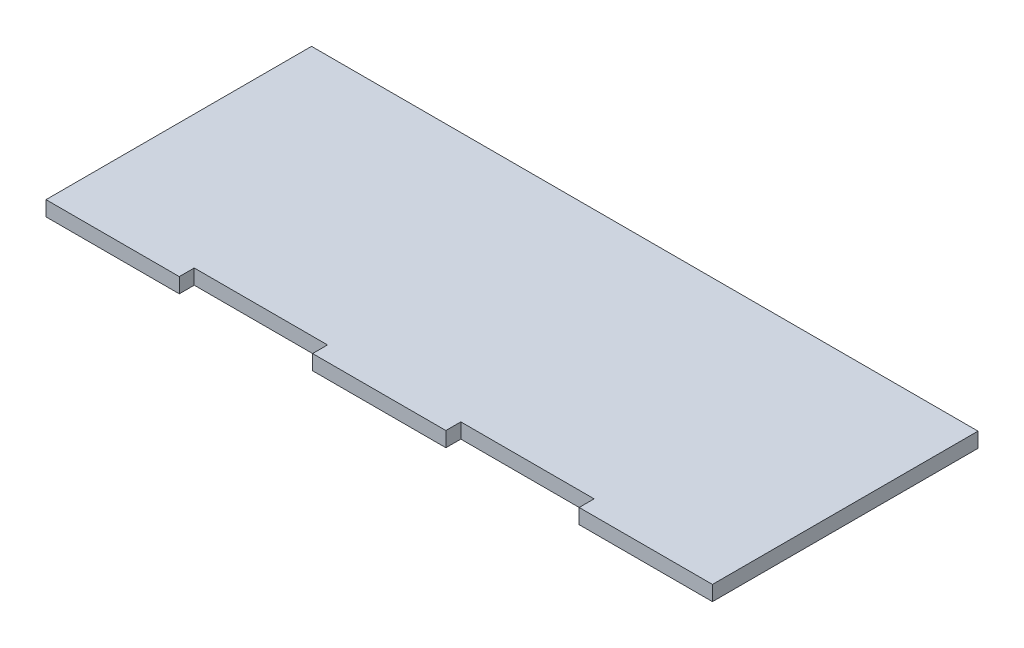
SolidWorks part; units mm, degrees
ref_plane "Front Plane" through (0, 0, 0) normal (0, 0, 1) x (1, 0, 0)
ref_plane "Top Plane" through (0, 0, 0) normal (0, 1, 0) x (1, 0, 0)
ref_plane "Right Plane" through (0, 0, 0) normal (1, 0, 0) x (0, 0, -1)
sketch "Sketch1" plane through (0, 0, 0) normal (0, 1, 0) x (1, 0, 0)
  line L1 (-69.721, 206.5335) -> (440.0265, 206.5335)
  line L2 (-69.721, 206.5335) -> (-69.721, 3.4402)
  line L3 (-69.721, 3.4402) -> (440.0265, 3.4402)
  line L4 (440.0265, 206.5335) -> (440.0265, 3.4402)
  dimension "D1" = 509.7475
  dimension "D2" = 203.0933
extrude "Boss-Extrude1" add sketch "Sketch1" along normal blind 11.43
sketch "Sketch2" plane through (0, 0, 0) normal (0, -1, 0) x (1, 0, 0)
  line L0 (185.1528, -3.4402) -> (185.1528, -206.5335) construction
  line L1 (-69.721, -3.4402) -> (440.0265, -3.4402) construction
  line L2 (440.0265, -206.5335) -> (-69.721, -206.5335) construction
  line L3 (338.077, -14.8702) -> (236.1275, -14.8702)
  line L4 (-69.721, -206.5335) -> (-69.721, -3.4402) construction
  line L6 (236.1275, -3.4402) -> (236.1275, -14.8702)
  line L7 (32.2285, -3.4402) -> (134.178, -3.4402)
  line L8 (32.2285, -3.4402) -> (32.2285, -14.8702)
  line L9 (32.2285, -14.8702) -> (134.178, -14.8702)
  line L10 (134.178, -3.4402) -> (134.178, -14.8702)
  line L11 (338.077, -3.4402) -> (236.1275, -3.4402)
  line L12 (338.077, -3.4402) -> (338.077, -14.8702)
  dimension "D1" = 11.43
  dimension "D2" = 101.9495
  dimension "D3" = 101.9495
extrude "Cut-Extrude1" cut sketch "Sketch2" against normal through all
equation "\"D1@Sketch1\"=\"Base Length@Assembled Container.Assembly\""
equation "\"D2@Sketch1\"=\"Side Height@Assembled Container.Assembly\""
equation "\"D1@Boss-Extrude1\"=\"Acrylic Thickness@Assembled Container.Assembly\""
equation "\"D1@Sketch2\"=\"Acrylic Thickness@Assembled Container.Assembly\""
equation "\"D2@Sketch2\"=\"Lid Long Side Outer Cutout@Assembled Container.Assembly\""
equation "\"D3@Sketch2\"=\"Lid Long Side Overhang@Assembled Container.Assembly\""
